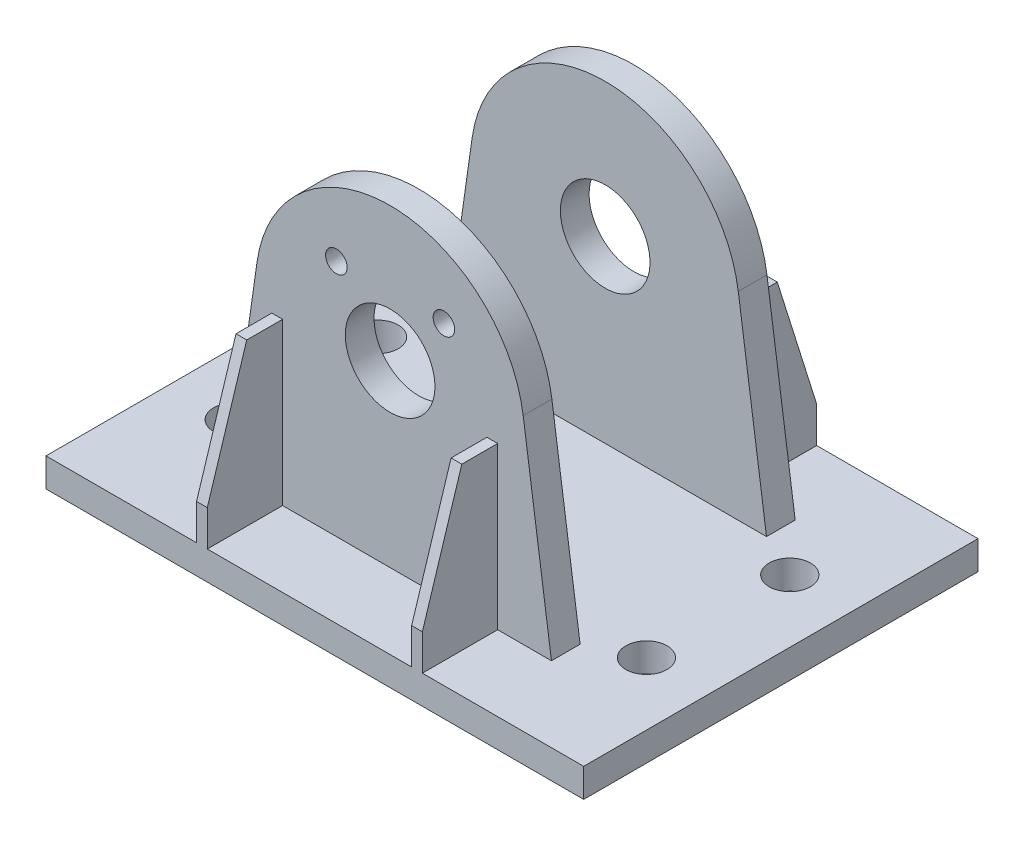
SolidWorks part; units mm, degrees
ref_plane "前视基准面" through (0, 0, 0) normal (0, 0, 1) x (1, 0, 0)
ref_plane "上视基准面" through (0, 0, 0) normal (0, 1, 0) x (1, 0, 0)
ref_plane "右视基准面" through (0, 0, 0) normal (1, 0, 0) x (0, 0, -1)
sketch "草图1" plane through (0, 0, 0) normal (0, 1, 0) x (1, 0, 0)
  line L1 (0, 0) -> (300, 0)
  line L2 (0, 0) -> (0, 220)
  line L3 (0, 220) -> (300, 220)
  line L4 (300, 0) -> (300, 220)
  dimension "D1" = 300
  dimension "D2" = 220
extrude "凸台-拉伸1" add sketch "草图1" along normal blind 16
sketch "草图2" plane through (0, 16, 0) normal (0, 1, 0) x (1, 0, 0)
  line L0 (150, 220) -> (150, 0) construction
  line L1 (300, 220) -> (0, 220) construction
  line L2 (0, 0) -> (300, 0) construction
  line L3 (0, 110) -> (300, 110) construction
  line L4 (0, 220) -> (0, 0) construction
  line L5 (300, 0) -> (300, 220) construction
  circle A0 centre (35, 150) radius 11.5
  dimension "D1" = 23
  dimension "D2" = 40
  dimension "D3" = 115
extrude "切除-拉伸1" cut sketch "草图2" against normal through all
pattern_linear "阵列(线性)1" count 2 spacing 230 along (1, 0, 0) count 2 spacing 80 along (0, 0, 1) of "切除-拉伸1"
sketch "草图3" plane through (0, 16, 0) normal (0, 1, 0) x (1, 0, 0)
  line L0 (0, 110) -> (300, 110) construction
  line L1 (60, 178) -> (240, 178)
  line L2 (60, 178) -> (60, 162)
  line L3 (60, 162) -> (240, 162)
  line L4 (240, 178) -> (240, 162)
  line L5 (0, 220) -> (0, 0) construction
  line L6 (300, 0) -> (300, 220) construction
  line L7 (150, 220) -> (150, 0) construction
  line L8 (300, 220) -> (0, 220) construction
  line L9 (0, 0) -> (300, 0) construction
  dimension "D1" = 16
  dimension "D2" = 180
  dimension "D3" = 52
  dimension "D4" = 90
extrude "凸台-拉伸2" add sketch "草图3" along normal blind 175
sketch "草图5" plane through (0, 0, -178) normal (0, 0, -1) x (-1, 0, 0)
  line L0 (-150, 191) -> (-150, 16) construction
  line L1 (-240, 191) -> (-60, 191) construction
  line L2 (-240, 16) -> (-60, 16) construction
  line L3 (-60, 16) -> (-75.7494, 126.5756)
  line L4 (-150, 191) -> (-60, 191)
  line L5 (-60, 191) -> (-60, 16)
  arc A0 (-75.7494, 126.5756) -> (-150, 191) centre (-150, 116) ccw
  dimension "D1" = 75
extrude "切除-拉伸2" cut sketch "草图5" against normal through all
sketch "草图7" plane through (0, 0, -178) normal (0, 0, -1) x (-1, 0, 0)
  line L0 (-150, 16) -> (-150, 191) construction
  line L1 (-240, 16) -> (-60, 16) construction
  line L2 (-224.2506, 126.5756) -> (-240, 16)
  line L3 (-240, 16) -> (-240, 191)
  line L4 (-240, 191) -> (-150, 191)
  arc A0 (-150, 191) -> (-224.2506, 126.5756) centre (-150, 116) ccw
  dimension "D1" = 75
extrude "切除-拉伸3" cut sketch "草图7" against normal through all
sketch "草图8" plane through (0, 0, -178) normal (0, 0, -1) x (-1, 0, 0)
  line L0 (-150, 16) -> (-150, 191) construction
  line L1 (-240, 16) -> (-60, 16) construction
  arc A0 (-75.7494, 126.5756) -> (-224.2506, 126.5756) centre (-150, 116) ccw construction
  circle A1 centre (-150, 116) radius 25
  dimension "D1" = 50
  dimension "D2" = 75
extrude "切除-拉伸4" cut sketch "草图8" against normal through all
pattern_linear "阵列(线性)3" count 2 spacing 120 along (0, 0, 1) of "凸台-拉伸2", "切除-拉伸2", "切除-拉伸3", "切除-拉伸4"
sketch "草图9" plane through (0, 0, -42) normal (0, 0, 1) x (1, 0, 0)
  line L0 (150, 16) -> (150, 191) construction
  line L1 (60, 16) -> (240, 16) construction
  circle A0 centre (120, 149) radius 6
  arc A2 (224.2506, 126.5756) -> (75.7494, 126.5756) centre (150, 116) ccw construction
  dimension "D1" = 12
  dimension "D2" = 30
  dimension "D3" = 133
extrude "切除-拉伸5" cut sketch "草图9" against normal blind 16
pattern_linear "阵列(线性)4" count 2 spacing 60 along (1, 0, 0) of "切除-拉伸5"
sketch "草图10" plane through (0, 16, 0) normal (0, 1, 0) x (1, 0, 0)
  line L0 (150, 0) -> (150, 220) construction
  line L1 (0, 0) -> (300, 0) construction
  line L2 (300, 220) -> (0, 220) construction
  line L4 (60, 42) -> (240, 42) construction
  line L5 (84, 42) -> (90, 42)
  line L6 (84, 42) -> (84, 0)
  line L7 (84, 0) -> (90, 0)
  line L8 (90, 42) -> (90, 0)
  dimension "D1" = 60
  dimension "D2" = 6
extrude "凸台-拉伸3" add sketch "草图10" along normal blind 90
pattern_linear "阵列(线性)5" count 2 spacing 120 along (1, 0, 0) count 2 spacing 178 along (0, 0, -1) of "凸台-拉伸3"
sketch "草图11" plane through (84, 0, 0) normal (-1, 0, 0) x (0, 0, 1)
  line L0 (0, 106) -> (-22, 106)
  line L1 (-42, 106) -> (0, 106) construction
  line L2 (-22, 106) -> (0, 36)
  line L3 (0, 106) -> (0, 16) construction
  line L4 (0, 36) -> (0, 106)
  line L5 (-220, 106) -> (-220, 36)
  line L6 (-220, 106) -> (-220, 16) construction
  line L7 (-220, 36) -> (-198, 106)
  line L8 (-220, 106) -> (-178, 106) construction
  line L9 (-198, 106) -> (-220, 106)
  dimension "D1" = 20
  dimension "D2" = 20
extrude "切除-拉伸6" cut sketch "草图11" against normal through all
